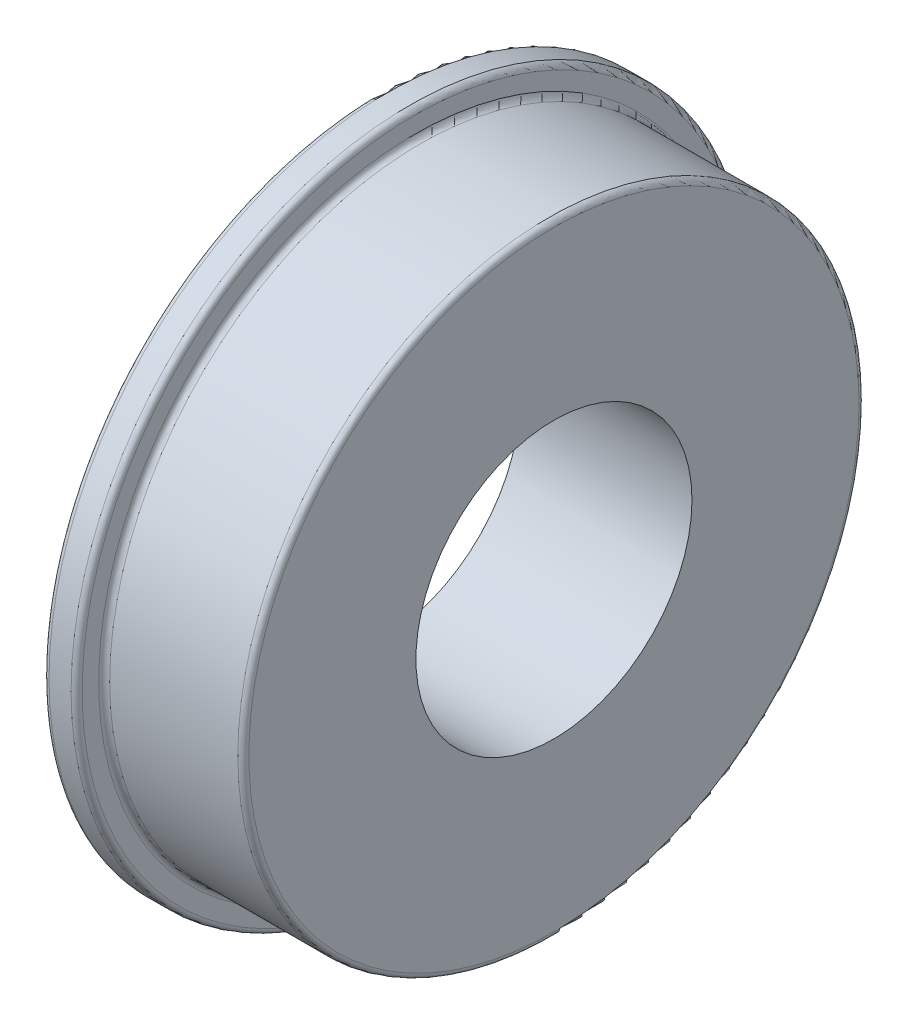
SolidWorks part; units mm, degrees
ref_plane "Front Plane" through (0, 0, 0) normal (0, 0, 1) x (1, 0, 0)
ref_plane "Top Plane" through (0, 0, 0) normal (0, 1, 0) x (1, 0, 0)
ref_plane "Right Plane" through (0, 0, 0) normal (1, 0, 0) x (0, 0, -1)
sketch "Sketch1" plane through (0, 0, 0) normal (1, 0, 0) x (0, 0, -1)
  circle A0 centre (0, 0) radius 15.5575
  dimension "D1" = 31.115
extrude "Boss-Extrude1" add sketch "Sketch1" along normal blind 1.524
sketch "Sketch2" plane through (1.524, 0, 0) normal (1, 0, 0) x (0, 0, -1)
  circle A0 centre (0, 0) radius 14.2875
  dimension "D1" = 28.575
extrude "Boss-Extrude2" add sketch "Sketch2" along normal blind 6.4008
sketch "Sketch3" plane through (7.9248, 0, 0) normal (1, 0, 0) x (0, 0, -1)
  circle A0 centre (0, 0) radius 6.35
  dimension "D1" = 12.7
extrude "Cut-Extrude1" cut sketch "Sketch3" against normal through all
fillet "Fillet1" radius 0.254 4 edges at (1.524, 0, -15.5575) (0, 0, -15.5575) (1.524, 0, -14.2875) (7.9248, 0, -14.2875)
